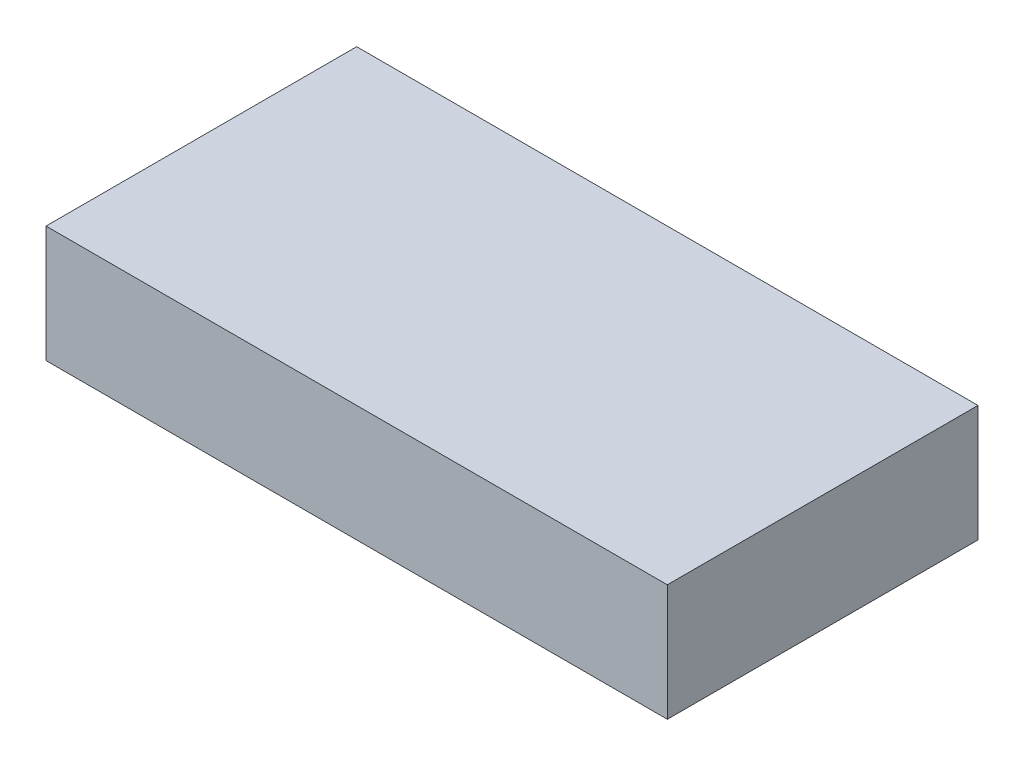
SolidWorks part; units mm, degrees
ref_plane "Front Plane" through (0, 0, 0) normal (0, 0, 1) x (1, 0, 0)
ref_plane "Top Plane" through (0, 0, 0) normal (0, 1, 0) x (1, 0, 0)
ref_plane "Right Plane" through (0, 0, 0) normal (1, 0, 0) x (0, 0, -1)
sketch "Sketch7" plane through (0, 0, 0) normal (0, 1, 0) x (1, 0, 0)
  line L1 (0, 0) -> (101.6, 0)
  line L2 (0, 0) -> (0, 50.8)
  line L3 (0, 50.8) -> (101.6, 50.8)
  line L4 (101.6, 0) -> (101.6, 50.8)
extrude "Extrude6" add sketch "Sketch7" against normal blind 19.05
sketch "Sketch8" plane through (0, 0, 0) normal (0, 1, 0) x (1, 0, 0)
  line L7 (28.4971, 43.0408) -> (83.8172, 35.2745)
  line L8 (28.4971, 7.7592) -> (83.8172, 15.5255)
  arc A0 (28.4971, 43.0408) -> (28.4971, 7.7592) centre (26.0205, 25.4) ccw
  arc A1 (83.8172, 15.5255) -> (83.8172, 35.2745) centre (82.431, 25.4) ccw
